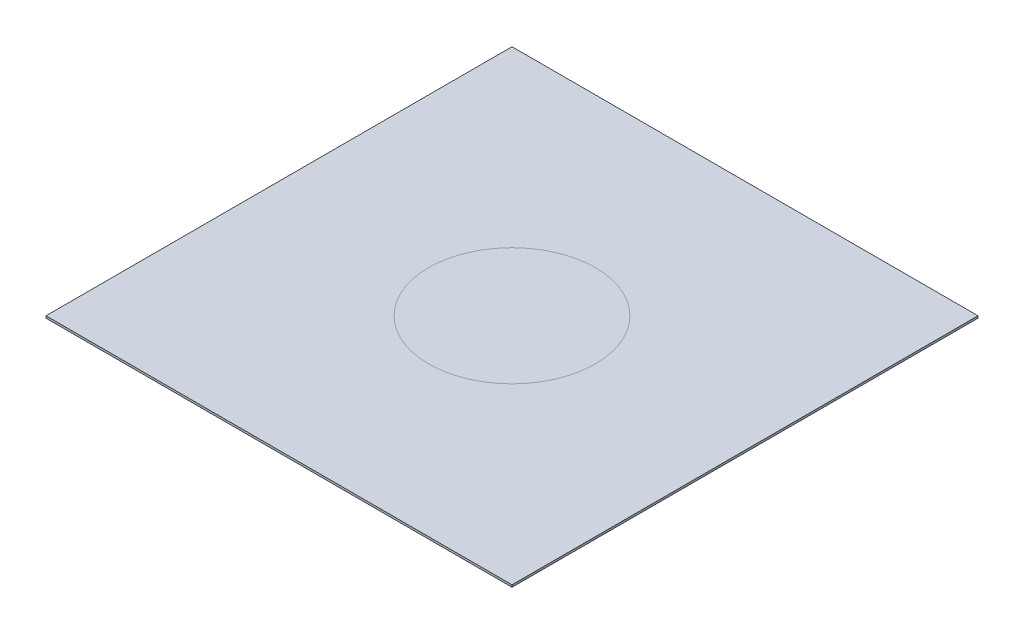
SolidWorks part; units mm, degrees
material "Alumina"
ref_plane "Front Plane" through (0, 0, 0) normal (0, 0, 1) x (1, 0, 0)
ref_plane "Top Plane" through (0, 0, 0) normal (0, 1, 0) x (1, 0, 0)
ref_plane "Right Plane" through (0, 0, 0) normal (1, 0, 0) x (0, 0, -1)
sketch "Sketch1" plane through (0, 0, 0) normal (0, 1, 0) x (1, 0, 0)
  line L1 (-69.85, -69.85) -> (69.85, -69.85)
  line L2 (-69.85, -69.85) -> (-69.85, 69.85)
  line L3 (-69.85, 69.85) -> (69.85, 69.85)
  line L4 (69.85, -69.85) -> (69.85, 69.85)
  line L5 (-69.85, -69.85) -> (69.85, 69.85) construction
  line L6 (-69.85, 69.85) -> (69.85, -69.85) construction
  point P0 (0, 0)
  dimension "D1" = 139.7
extrude "Boss-Extrude1" add sketch "Sketch1" along normal mid plane 0.64
sketch "Sketch2" plane through (0, 0.32, 0) normal (0, 1, 0) x (1, 0, 0)
  circle A0 centre (0, 0) radius 25
  dimension "D1" = 50
split line "Split Line1"
